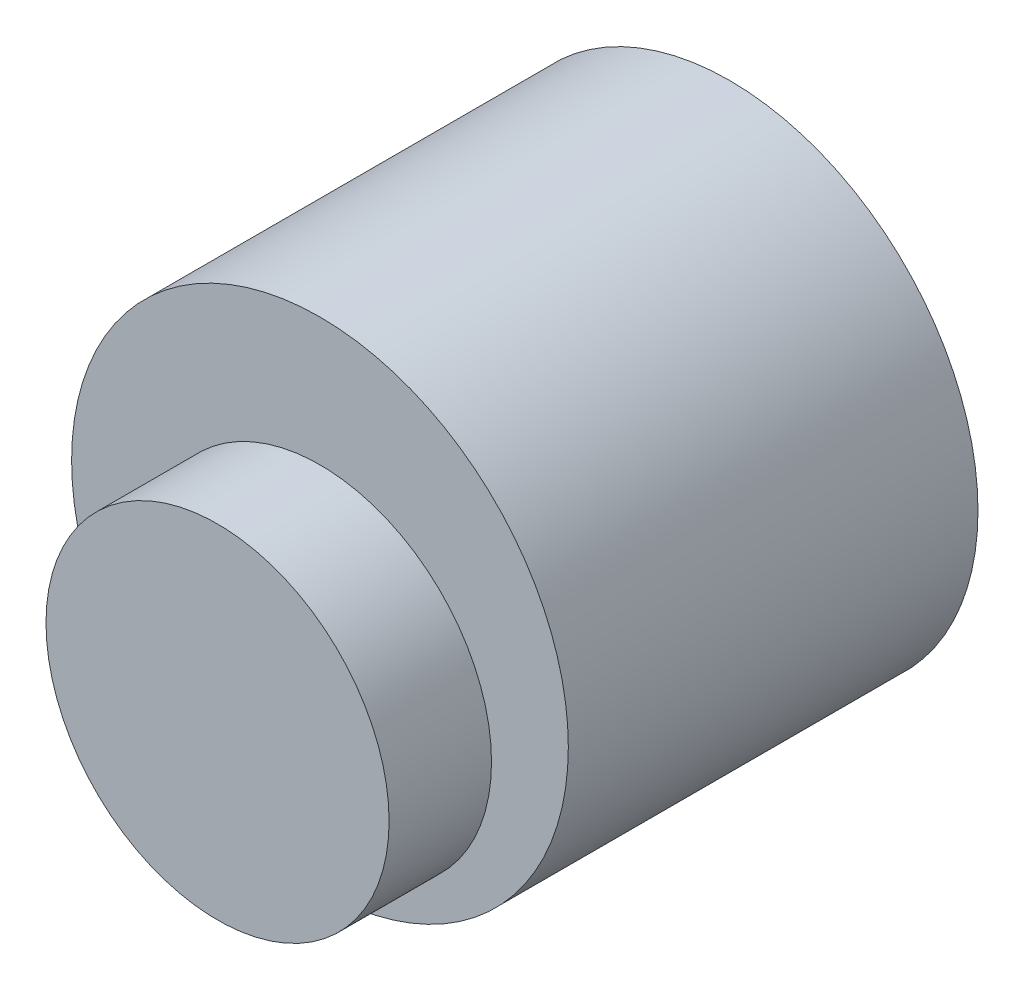
SolidWorks part; units mm, degrees
ref_plane "Plan de face" through (0, 0, 0) normal (0, 0, 1) x (1, 0, 0)
ref_plane "Plan de dessus" through (0, 0, 0) normal (0, 1, 0) x (1, 0, 0)
ref_plane "Plan de droite" through (0, 0, 0) normal (1, 0, 0) x (0, 0, -1)
sketch "Esquisse1" plane through (0, 0, 0) normal (0, 0, 1) x (1, 0, 0)
  line L0 (-1.5, 2) -> (1.5, 2)
  arc A0 (-1.5, 2) -> (1.5, 2) centre (0, 0) ccw
  circle A2 centre (0, 1) radius 4.85
  dimension "D1" = 2.5
  dimension "D2" = 2
  dimension "D4" = 9.7
  dimension "D5" = 1
extrude "Boss.-Extru.1" add sketch "Esquisse1" along normal blind 8
sketch "Esquisse2" plane through (0, 0, 8) normal (0, 0, 1) x (1, 0, 0)
  circle A0 centre (0, 0) radius 3.35
  dimension "D1" = 6.7
extrude "Boss.-Extru.2" add sketch "Esquisse2" along normal blind 2
